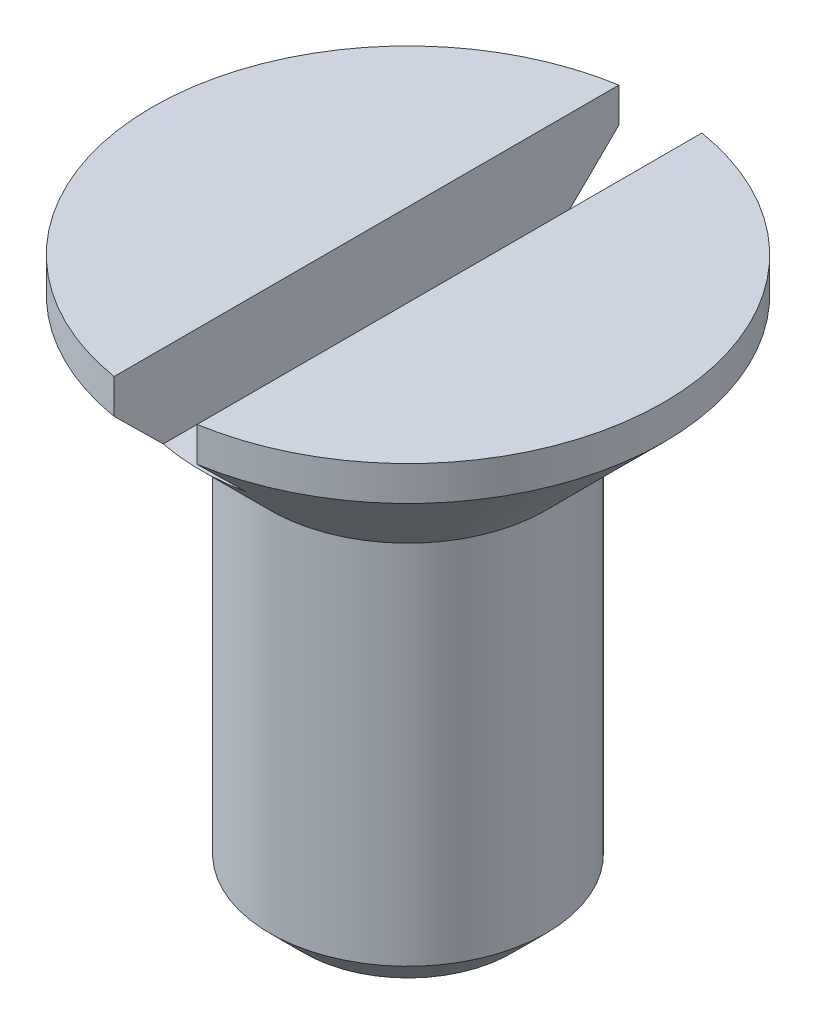
SolidWorks part; units mm, degrees
ref_plane "Спереди" through (0, 0, 0) normal (0, 0, 1) x (1, 0, 0)
ref_plane "Сверху" through (0, 0, 0) normal (0, 1, 0) x (1, 0, 0)
ref_plane "Справа" through (0, 0, 0) normal (1, 0, 0) x (0, 0, -1)
sketch "Эскиз1" plane through (0, 0, 0) normal (0, 0, 1) x (1, 0, 0)
  line L0 (0, 0) -> (-1.5, 0)
  line L1 (-1.5, 0) -> (-2, 0.5)
  line L2 (-2, 0.5) -> (-2, 5.8)
  line L3 (-2, 5.8) -> (-3.7, 7.5)
  line L4 (-3.7, 7.5) -> (-3.7, 8)
  line L5 (-3.7, 8) -> (0, 8)
  line L6 (0, 8) -> (0, 0)
  dimension "D1" = 2
  dimension "D2" = 45
  dimension "D3" = 1.5
  dimension "D4" = 8
  dimension "D5" = 45
  dimension "D6" = 2.2
  dimension "D7" = 3.7
revolve "Повернуть1" add sketch "Эскиз1" angle 360 about L6
sketch "Эскиз2" plane through (0, 0, 0) normal (0, 0, 1) x (1, 0, 0)
  line L0 (0, 0) -> (0, 8) construction
  line L1 (3.7, 8) -> (-3.7, 8) construction
  line L3 (-0.6, 8) -> (0.6, 8)
  line L4 (-0.6, 8) -> (-0.6, 6.8)
  line L5 (-0.6, 6.8) -> (0.6, 6.8)
  line L6 (0.6, 8) -> (0.6, 6.8)
  dimension "D1" = 1.2
  dimension "D2" = 1.2
extrude "Вырез-Вытянуть1" cut sketch "Эскиз2" against normal through all and the other way through all
